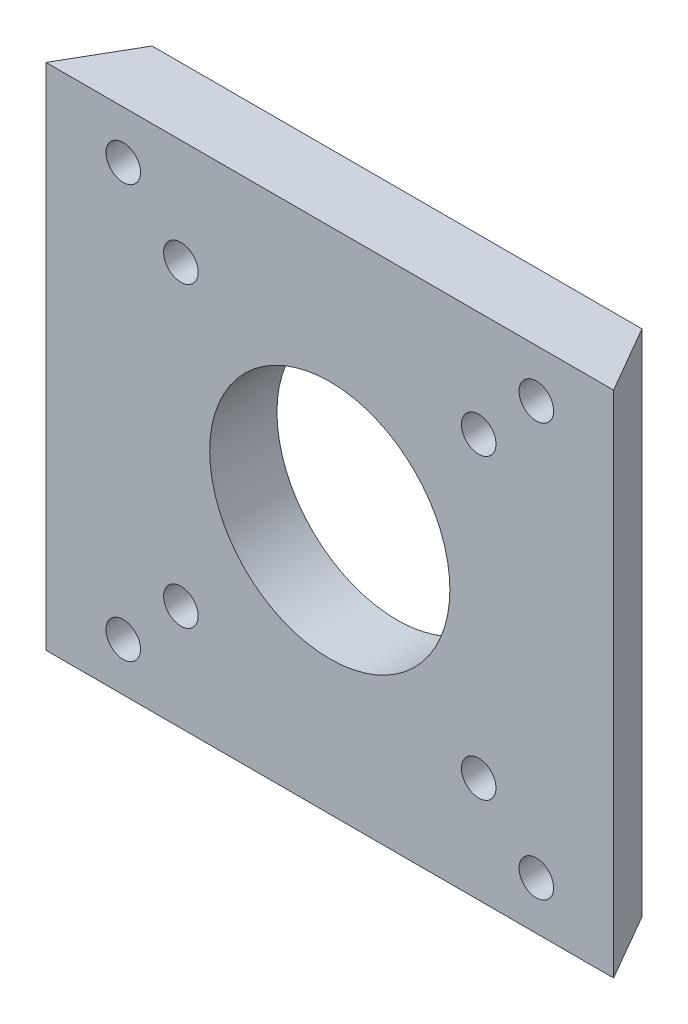
SolidWorks part; units mm, degrees
ref_plane "Front Plane" through (0, 0, 0) normal (0, 0, 1) x (1, 0, 0)
ref_plane "Top Plane" through (0, 0, 0) normal (0, 1, 0) x (1, 0, 0)
ref_plane "Right Plane" through (0, 0, 0) normal (1, 0, 0) x (0, 0, -1)
sketch "Sketch1" plane through (0, 0, 0) normal (0, 0, 1) x (1, 0, 0)
  line L1 (-25.5, -26.5) -> (25.5, -26.5)
  line L2 (-25.5, -26.5) -> (-25.5, 26.5)
  line L3 (-25.5, 26.5) -> (25.5, 26.5)
  line L4 (25.5, -26.5) -> (25.5, 26.5)
  line L5 (-25.5, -26.5) -> (25.5, 26.5) construction
  line L6 (-25.5, 26.5) -> (25.5, -26.5) construction
  point P0 (0, 0)
  dimension "D1" = 51
  dimension "D2" = 53
extrude "Boss-Extrude1" add sketch "Sketch1" along normal blind 7
sketch "Sketch2" plane through (0, 0, 0) normal (0, 0, 1) x (1, 0, 0)
  circle A0 centre (0, 0) radius 12.5
  dimension "D1" = 25
extrude "Cut-Extrude3" cut sketch "Sketch2" against normal blind 10 and the other way through all
sketch "Sketch3" plane through (0, 0, 7) normal (0, 0, 1) x (1, 0, 0)
  line L1 (15.5, -15.5) -> (-15.5, -15.5) construction
  line L2 (15.5, -15.5) -> (15.5, 15.5) construction
  line L3 (15.5, 15.5) -> (-15.5, 15.5) construction
  line L4 (-15.5, -15.5) -> (-15.5, 15.5) construction
  line L5 (15.5, -15.5) -> (-15.5, 15.5) construction
  line L6 (15.5, 15.5) -> (-15.5, -15.5) construction
  circle A0 centre (-15.5, 15.5) radius 1.8
  circle A1 centre (15.5, 15.5) radius 1.8
  circle A2 centre (15.5, -15.5) radius 1.8
  circle A3 centre (-15.5, -15.5) radius 1.8
  point P0 (0, 0)
  dimension "D3" = 3.6
  dimension "D1" = 31
  dimension "D2" = 31
extrude "Cut-Extrude4" cut sketch "Sketch3" against normal blind 10
sketch "Sketch4" plane through (0, 0, 7) normal (0, 0, 1) x (1, 0, 0)
  line L1 (21.5, -21.5) -> (-21.5, -21.5) construction
  line L2 (21.5, -21.5) -> (21.5, 21.5) construction
  line L3 (21.5, 21.5) -> (-21.5, 21.5) construction
  line L4 (-21.5, -21.5) -> (-21.5, 21.5) construction
  line L5 (21.5, -21.5) -> (-21.5, 21.5) construction
  line L6 (21.5, 21.5) -> (-21.5, -21.5) construction
  circle A0 centre (-21.5, 21.5) radius 1.8
  circle A1 centre (21.5, 21.5) radius 1.8
  circle A2 centre (21.5, -21.5) radius 1.8
  circle A3 centre (-21.5, -21.5) radius 1.8
  point P0 (0, 0)
  dimension "D3" = 3.6
  dimension "D1" = 43
  dimension "D2" = 43
extrude "Cut-Extrude5" cut sketch "Sketch4" against normal blind 11
sketch "Sketch5" plane through (0, 26.5, 0) normal (0, 1, 0) x (1, 0, 0)
  line L0 (-25.5, -7) -> (-29.5415, -7)
  line L1 (-29.5415, -7) -> (-25.5, 0)
  line L2 (-25.5, 0) -> (-25.5, -7)
  line L3 (25.5, 0) -> (25.5, -7)
  line L4 (25.5, -7) -> (29.5415, -7)
  line L5 (29.5415, -7) -> (25.5, 0)
  dimension "D1" = 60
  dimension "D2" = 60
extrude "Boss-Extrude2" add sketch "Sketch5" against normal up to surface (53 mm away) up to face at (0, -26.5, 3.5)
sketch "Sketch6" plane through (0, 0, 0) normal (0, 0, -1) x (-1, 0, 0)
  circle A0 centre (-15.5, 15.5) radius 4
  circle A1 centre (15.5, 15.5) radius 4
  circle A2 centre (15.5, -15.5) radius 4
  circle A3 centre (-15.5, -15.5) radius 4
  dimension "D1" = 8
extrude "Cut-Extrude6" cut sketch "Sketch6" against normal blind 4
